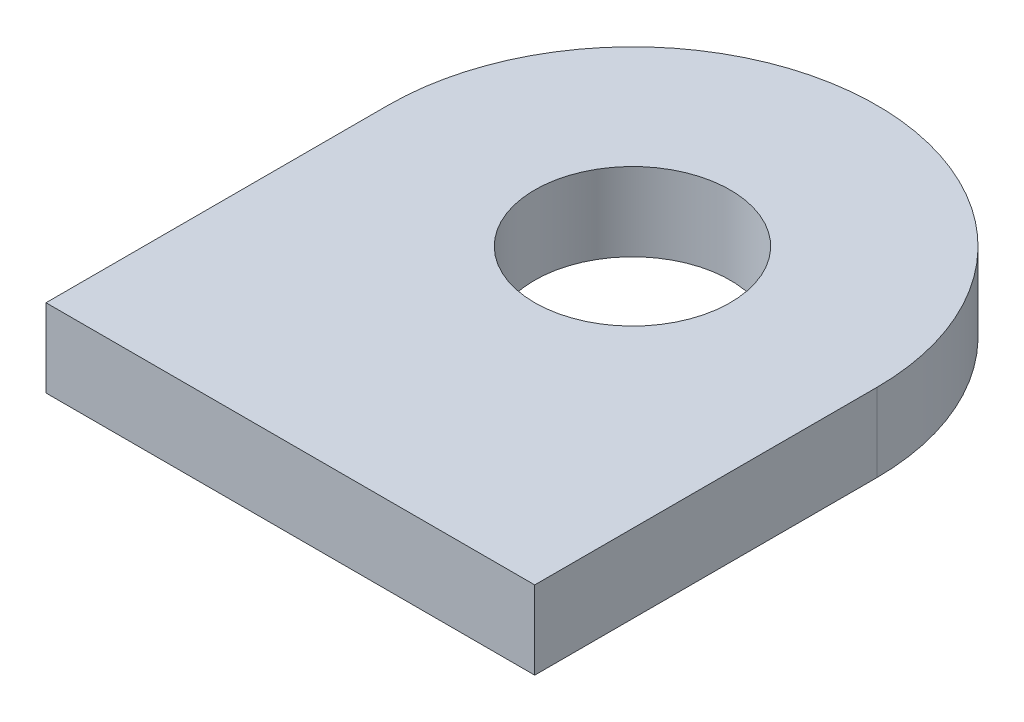
SolidWorks part; units mm, degrees
material "6061 Alloy"
ref_plane "Front Plane" through (0, 0, 0) normal (0, 0, 1) x (1, 0, 0)
ref_plane "Top Plane" through (0, 0, 0) normal (0, 1, 0) x (1, 0, 0)
ref_plane "Right Plane" through (0, 0, 0) normal (1, 0, 0) x (0, 0, -1)
sketch "Sketch1" plane through (0, 0, 0) normal (0, 1, 0) x (1, 0, 0)
  line L0 (-7.9375, -11.1125) -> (7.9375, -11.1125)
  line L1 (7.9375, -11.1125) -> (7.9375, 0)
  line L2 (-7.9375, 0) -> (-7.9375, -11.1125)
  arc A0 (7.9375, 0) -> (-7.9375, 0) centre (0, 0) ccw
  point P3 (0, 7.9375)
  dimension "D1" = 15.875
  dimension "D2" = 19.05
extrude "Boss-Extrude1" add sketch "Sketch1" along normal blind 2.54
hole_wizard "1/4 (0.25) Diameter Hole1" positions "Sketch4" profile "Sketch5" hole size "1/4" standard "ANSI Inch" end condition through all
sketch "Sketch4" plane through (0, 2.54, 0) normal (0, 1, 0) x (1, 0, 0)
  point P0 (0, 0)
sketch "Sketch5" plane through (0, 2.54, 0) normal (1, 0, 0) x (0, 0, 1)
  line L0 (0, 0) -> (0, 2.54)
  line L1 (0, 2.54) -> (3.175, 2.54)
  line L2 (3.175, 2.54) -> (3.175, 0)
  line L5 (3.175, 0) -> (0, 0)
  line L11 (0, -6.35) -> (0, 107.95) construction
  dimension "Thru Hole Dia." = 6.35
  dimension "Thru Hole Depth" = 2.54
